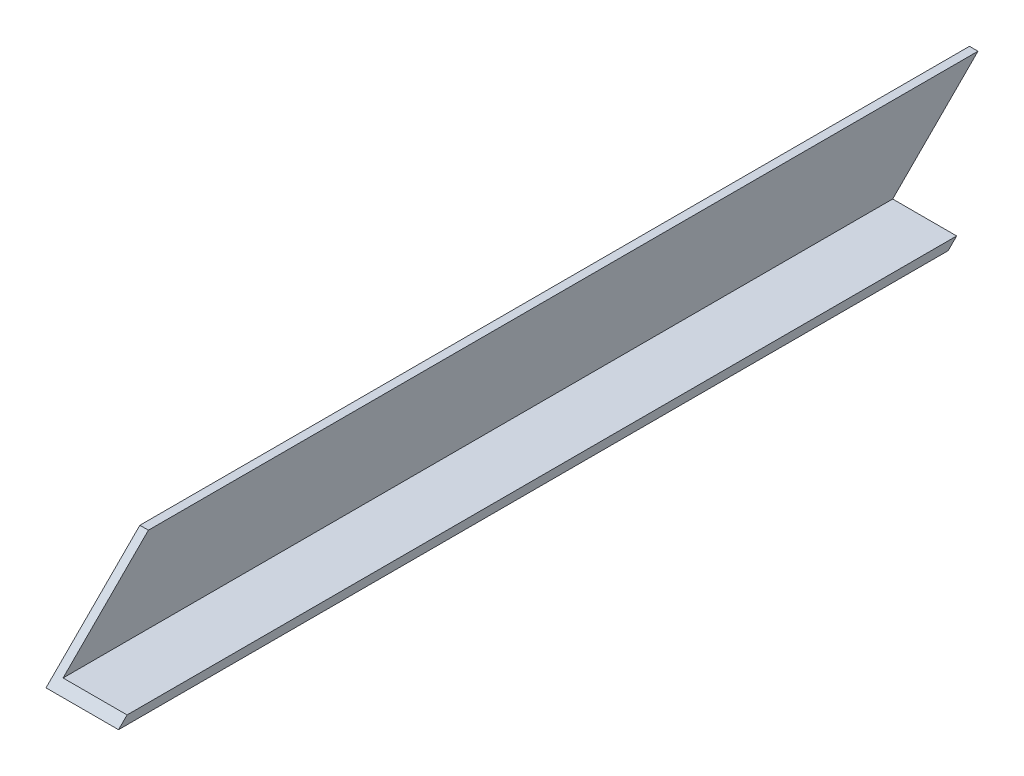
SolidWorks part; units mm, degrees
ref_plane "Front Plane" through (0, 0, 0) normal (0, 0, 1) x (1, 0, 0)
ref_plane "Top Plane" through (0, 0, 0) normal (0, 1, 0) x (1, 0, 0)
ref_plane "Right Plane" through (0, 0, 0) normal (1, 0, 0) x (0, 0, -1)
sketch "Sketch1" plane through (0, 0, 0) normal (0, 0, 1) x (1, 0, 0)
  line L0 (0, 0) -> (0, 22)
  line L1 (0, 22) -> (2, 22)
  line L2 (2, 22) -> (2, 2)
  line L3 (2, 2) -> (17, 2)
  line L4 (17, 2) -> (17, 0)
  line L5 (17, 0) -> (0, 0)
  dimension "D1" = 22
  dimension "D2" = 17
  dimension "D3" = 2
  dimension "D4" = 2
extrude "Boss-Extrude1" add sketch "Sketch1" along normal blind 250
sketch "Sketch2" plane through (2, 0, 0) normal (1, 0, 0) x (0, 0, -1)
  line L0 (-250, 22) -> (-250, 0)
  line L1 (-250, 0) -> (-228, 22)
  line L2 (-250, 22) -> (0, 22) construction
  line L3 (-228, 22) -> (-250, 22)
  line L4 (0, 22) -> (-33.5456, 22)
  line L5 (-33.5456, 22) -> (-55.5456, 0)
  line L6 (-250, 0) -> (0, 0) construction
  line L7 (-55.5456, 0) -> (0, 0)
  line L8 (0, 0) -> (0, 22)
  dimension "D1" = 45
  dimension "D2" = 137.5
extrude "Cut-Extrude1" cut sketch "Sketch2" along normal through all both and the other way through all
